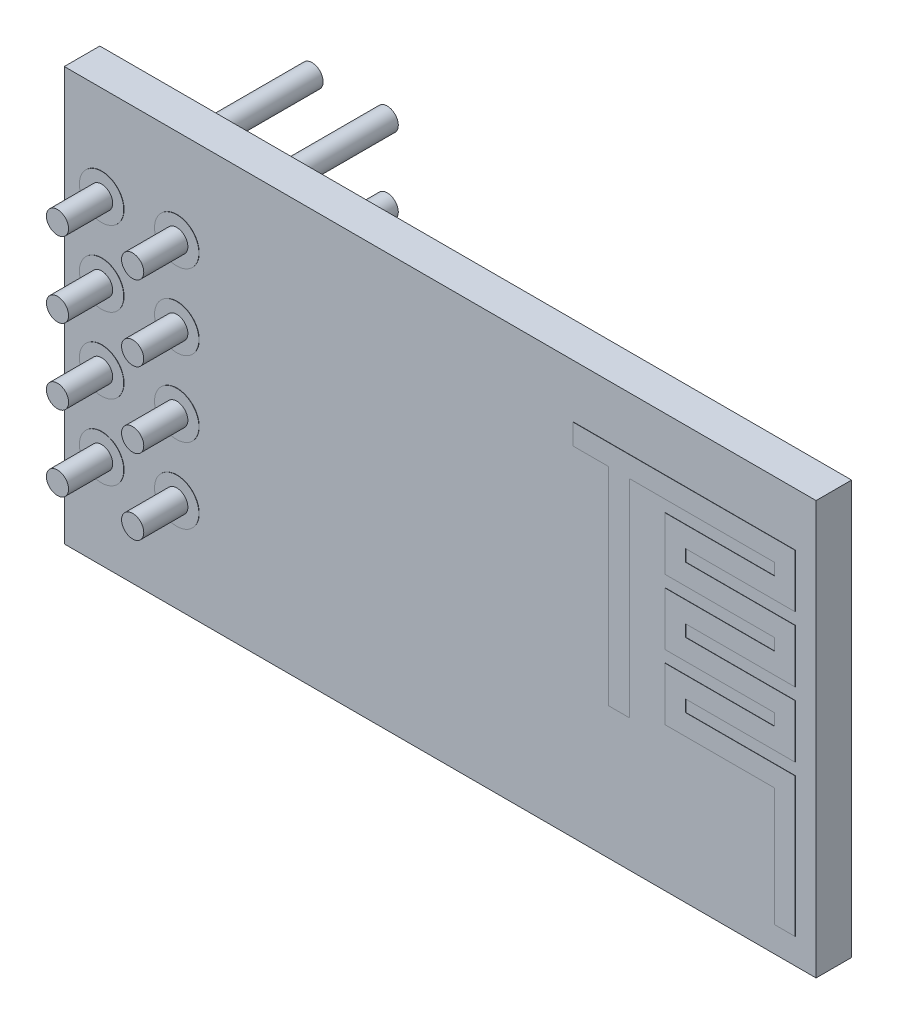
SolidWorks part; units mm, degrees
ref_plane "Front Plane" through (0, 0, 0) normal (0, 0, 1) x (1, 0, 0)
ref_plane "Top Plane" through (0, 0, 0) normal (0, 1, 0) x (1, 0, 0)
ref_plane "Right Plane" through (0, 0, 0) normal (1, 0, 0) x (0, 0, -1)
sketch "Sketch2" plane through (0, 0, 0) normal (0, 0, 1) x (1, 0, 0)
  line L1 (0, 0) -> (25.4, 0)
  line L2 (0, 0) -> (0, 13.97)
  line L3 (0, 13.97) -> (25.4, 13.97)
  line L4 (25.4, 0) -> (25.4, 13.97)
  dimension "D1" = 25.4
  dimension "D2" = 13.97
extrude "Boss-Extrude1" add sketch "Sketch2" along normal blind 1.2
sketch "Sketch3" plane through (0, 0, 1.2) normal (0, 0, 1) x (1, 0, 0)
  line L0 (0, 13.97) -> (0, 0) construction
  line L1 (25.4, 13.97) -> (0, 13.97) construction
  circle A0 centre (1.27, 10.795) radius 0.75
  circle A1 centre (3.81, 10.795) radius 0.75
  circle A2 centre (3.81, 8.255) radius 0.75
  circle A3 centre (3.81, 5.715) radius 0.75
  circle A4 centre (3.81, 3.175) radius 0.75
  circle A5 centre (1.27, 8.255) radius 0.75
  circle A6 centre (1.27, 5.715) radius 0.75
  circle A7 centre (1.27, 3.175) radius 0.75
  dimension "D1" = 1.27
  dimension "D3" = 1.5
  dimension "D2" = 3.175
  dimension "D4" = 2
  dimension "D5" = 4
extrude "Boss-Extrude2" add sketch "Sketch3" along normal blind 0.01
sketch "Sketch4" plane through (0, 0, 1.2) normal (0, 0, 1) x (1, 0, 0)
  circle A0 centre (1.27, 10.795) radius 0.375
  circle A1 centre (3.81, 10.795) radius 0.375
  circle A2 centre (3.81, 8.255) radius 0.375
  circle A3 centre (3.81, 5.715) radius 0.375
  circle A4 centre (3.81, 3.175) radius 0.375
  circle A5 centre (1.27, 8.255) radius 0.375
  circle A6 centre (1.27, 5.715) radius 0.375
  circle A7 centre (1.27, 3.175) radius 0.375
  dimension "D1" = 0.75
  dimension "D2" = 2
  dimension "D3" = 4
extrude "Boss-Extrude3" add sketch "Sketch4" along normal blind 1.5 and the other way blind 7.1
sketch "Sketch5" plane through (0, 0, 1.2) normal (0, 0, 1) x (1, 0, 0)
  line L0 (17.2, 12.17) -> (24.7, 12.17)
  line L1 (24.7, 12.17) -> (24.7, 10.37)
  line L2 (24.7, 10.37) -> (21, 10.37)
  line L3 (21, 10.37) -> (21, 9.97)
  line L4 (21, 9.97) -> (24.7, 9.97)
  line L5 (24.7, 9.97) -> (24.7, 8.17)
  line L6 (24.7, 8.17) -> (21, 8.17)
  line L7 (21, 8.17) -> (21, 7.77)
  line L8 (21, 7.77) -> (24.7, 7.77)
  line L9 (24.7, 7.77) -> (24.7, 5.97)
  line L10 (24.7, 5.97) -> (21, 5.97)
  line L11 (21, 5.97) -> (21, 5.57)
  line L12 (21, 5.57) -> (24.7, 5.57)
  line L13 (24.7, 5.57) -> (24.7, 0.87)
  line L14 (24.7, 0.87) -> (24, 0.87)
  line L15 (24, 0.87) -> (24, 4.87)
  line L16 (24, 4.87) -> (20.3, 4.87)
  line L17 (20.3, 4.87) -> (20.3, 6.67)
  line L18 (20.3, 6.67) -> (24, 6.67)
  line L19 (24, 6.67) -> (24, 7.07)
  line L20 (24, 7.07) -> (20.3, 7.07)
  line L21 (20.3, 7.07) -> (20.3, 8.87)
  line L22 (20.3, 8.87) -> (24, 8.87)
  line L23 (24, 8.87) -> (24, 9.27)
  line L24 (24, 9.27) -> (20.3, 9.27)
  line L25 (20.3, 9.27) -> (20.3, 11.07)
  line L26 (20.3, 11.07) -> (24, 11.07)
  line L27 (24, 11.07) -> (24, 11.47)
  line L28 (24, 11.47) -> (19.1, 11.47)
  line L29 (19.1, 11.47) -> (19.1, 4.47)
  line L30 (19.1, 4.47) -> (18.4, 4.47)
  line L31 (18.4, 4.47) -> (18.4, 11.47)
  line L32 (18.4, 11.47) -> (17.2, 11.47)
  line L33 (17.2, 11.47) -> (17.2, 12.17)
  line L34 (25.4, 13.97) -> (0, 13.97) construction
  line L35 (25.4, 0) -> (25.4, 13.97) construction
  point P36 (18.75, 4.47)
  dimension "D1" = 0.7
  dimension "D2" = 0.7
  dimension "D3" = 0.7
  dimension "D4" = 0.7
  dimension "D5" = 0.7
  dimension "D6" = 0.7
  dimension "D7" = 0.7
  dimension "D8" = 0.7
  dimension "D9" = 0.7
  dimension "D10" = 0.7
  dimension "D11" = 1.8
  dimension "D12" = 0.4
  dimension "D13" = 0.4
  dimension "D14" = 0.4
  dimension "D15" = 0.4
  dimension "D16" = 0.4
  dimension "D17" = 0.4
  dimension "D18" = 7
  dimension "D19" = 4
  dimension "D20" = 0.7
  dimension "D21" = 1.2
  dimension "D22" = 7.5
  dimension "D23" = 1.2
extrude "Boss-Extrude4" add sketch "Sketch5" along normal blind 0.01
sketch "Sketch6" plane through (0, 0, 0) normal (0, 0, -1) x (-1, 0, 0)
  line L0 (-25.4, 13.97) -> (0, 13.97) construction
  line L1 (-5.1, 11.47) -> (-0.1, 11.47)
  line L2 (-5.1, 11.47) -> (-5.1, 2.5)
  line L3 (-5.1, 2.5) -> (-0.1, 2.5)
  line L4 (-0.1, 11.47) -> (-0.1, 2.5)
  line L5 (0, 0) -> (-25.4, 0) construction
  line L6 (0, 13.97) -> (0, 0) construction
  dimension "D1" = 2.5
  dimension "D2" = 2.5
  dimension "D3" = 0.1
  dimension "D4" = 5
extrude "Boss-Extrude5" add sketch "Sketch6" along normal blind 2.2 separate body
